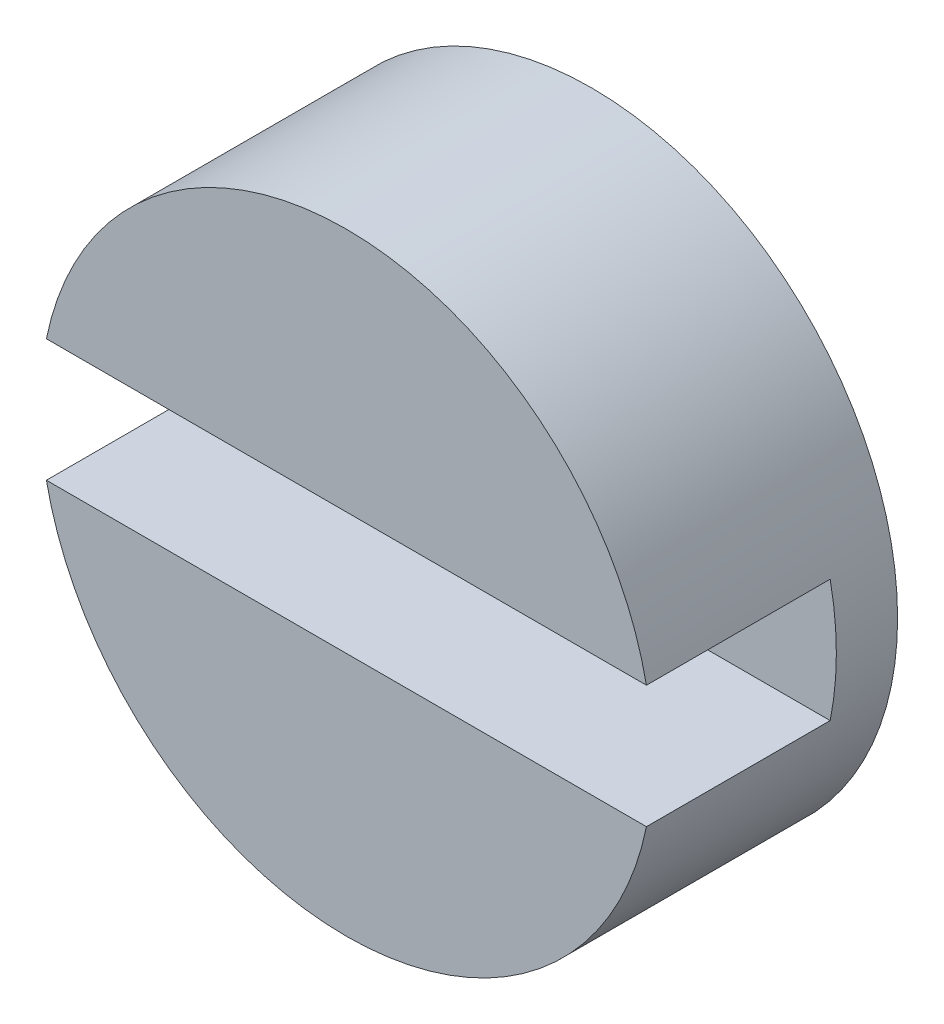
SolidWorks part; units mm, degrees
ref_plane "Front Plane" through (0, 0, 0) normal (0, 0, 1) x (1, 0, 0)
ref_plane "Top Plane" through (0, 0, 0) normal (0, 1, 0) x (1, 0, 0)
ref_plane "Right Plane" through (0, 0, 0) normal (1, 0, 0) x (0, 0, -1)
sketch "Sketch1" plane through (0, 0, 0) normal (0, 0, 1) x (1, 0, 0)
  circle A0 centre (0, 0) radius 25
  dimension "D1" = 50
extrude "Boss-Extrude1" add sketch "Sketch1" along normal blind 20
sketch "Sketch2" plane through (0, 0, 0) normal (1, 0, 0) x (0, 0, -1)
  line L0 (-20, 25) -> (-20, -25) construction
  line L1 (-35, -5) -> (-5, -5)
  line L2 (-35, -5) -> (-35, 5)
  line L3 (-35, 5) -> (-5, 5)
  line L4 (-5, -5) -> (-5, 5)
  line L5 (-35, -5) -> (-5, 5) construction
  line L6 (-35, 5) -> (-5, -5) construction
  point P0 (-20, 0)
  dimension "D1" = 10
  dimension "D2" = 15
extrude "Cut-Extrude1" cut sketch "Sketch2" against normal through all both and the other way through all
